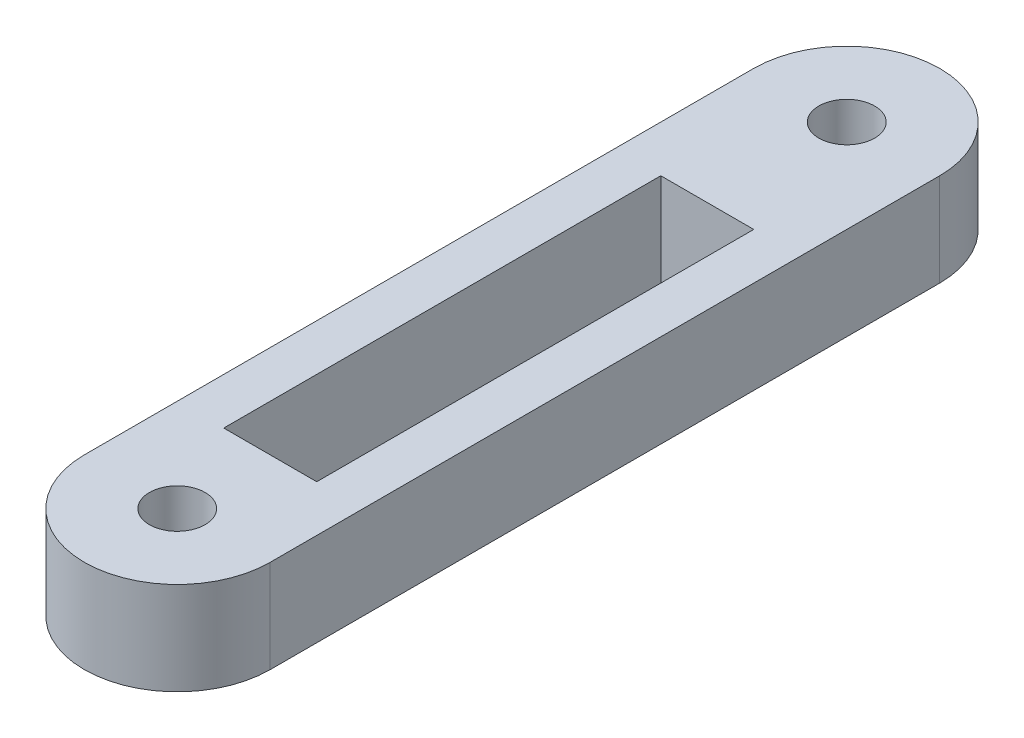
SolidWorks part; units mm, degrees
ref_plane "前视基准面" through (0, 0, 0) normal (0, 0, 1) x (1, 0, 0)
ref_plane "上视基准面" through (0, 0, 0) normal (0, 1, 0) x (1, 0, 0)
ref_plane "右视基准面" through (0, 0, 0) normal (1, 0, 0) x (0, 0, -1)
sketch "草图2" plane through (0, 0, 0) normal (0, 1, 0) x (1, 0, 0)
  line L0 (0, 18) -> (0, -18) construction
  line L1 (5, 18) -> (5, -18)
  line L2 (-5, 18) -> (-5, -18)
  arc A0 (5, 18) -> (-5, 18) centre (0, 18) ccw
  arc A1 (-5, -18) -> (5, -18) centre (0, -18) ccw
  point P3 (0, 0)
  dimension "D2" = 5
  dimension "D1" = 36
extrude "凸台-拉伸1" add sketch "草图2" along normal blind 5
sketch "草图3" plane through (0, 0, 0) normal (0, -1, 0) x (1, 0, 0)
  line L0 (0, -1000) -> (0, 49000) construction
  line L1 (-2.5, -10.5) -> (2.5, -10.5)
  line L2 (-2.5, -10.5) -> (-2.5, 13)
  line L3 (-2.5, 13) -> (2.5, 13)
  line L4 (2.5, -10.5) -> (2.5, 13)
  point P0 (0, 0)
  dimension "D1" = 5
  dimension "D2" = 5
  dimension "D3" = 7.5
extrude "切除-拉伸1" cut sketch "草图3" against normal blind 5
sketch "草图4" plane through (0, 0, 0) normal (0, -1, 0) x (1, 0, 0)
  line L0 (-1000, 0) -> (49000, 0) construction
  circle A0 centre (0, 18) radius 1.5
  arc A1 (5, 18) -> (-5, 18) centre (0, 18) ccw construction
  circle A2 centre (0, -18) radius 1.5
  dimension "D1" = 3
extrude "切除-拉伸2" cut sketch "草图4" against normal blind 5
